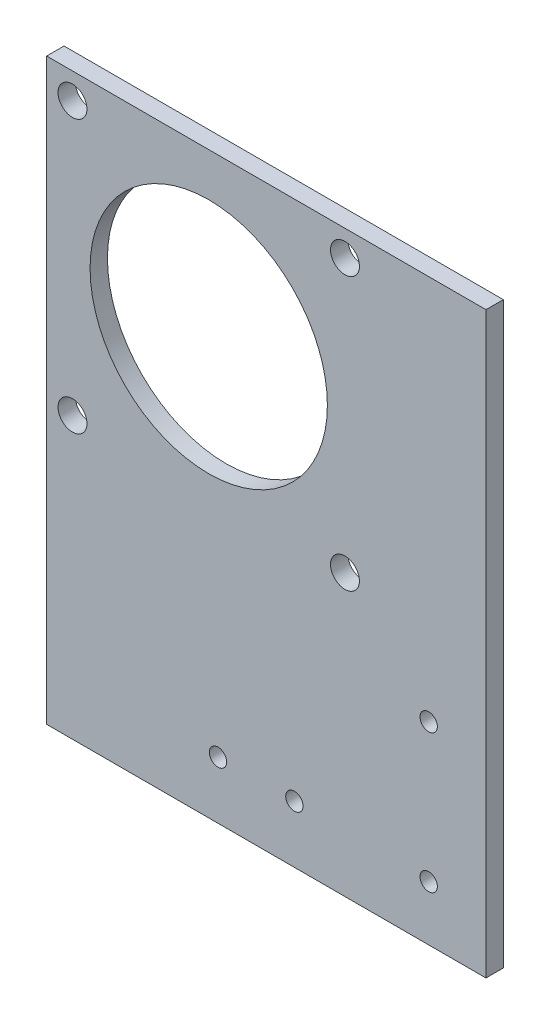
SolidWorks part; units mm, degrees
ref_plane "Front Plane" through (0, 0, 0) normal (0, 0, 1) x (1, 0, 0)
ref_plane "Top Plane" through (0, 0, 0) normal (0, 1, 0) x (1, 0, 0)
ref_plane "Right Plane" through (0, 0, 0) normal (1, 0, 0) x (0, 0, -1)
sketch "Sketch1" plane through (0, 0, 0) normal (0, 0, 1) x (1, 0, 0)
  line L1 (0, 0) -> (75.9, 0)
  line L2 (0, 0) -> (0, 100)
  line L3 (0, 100) -> (75.9, 100)
  line L4 (75.9, 0) -> (75.9, 100)
  dimension "D1" = 75.9
  dimension "D2" = 100
extrude "Boss-Extrude1" add sketch "Sketch1" along normal blind 3
sketch "Sketch2" plane through (0, 0, 0) normal (0, 0, -1) x (-1, 0, 0)
  circle A0 centre (-51.5386, 95.5386) radius 2.5
  circle A1 centre (-4.4614, 95.5386) radius 2.5
  circle A2 centre (-4.4614, 48.4614) radius 2.5
  circle A3 centre (-51.5386, 48.4614) radius 2.5
  dimension "D1" = 5
extrude "Cut-Extrude1" cut sketch "Sketch2" against normal blind 10
sketch "Sketch5" plane through (0, 0, 3) normal (0, 0, 1) x (1, 0, 0)
  line L0 (66, 0) -> (66, 100) construction
  line L1 (0, 0) -> (75.9, 0) construction
  line L2 (75.9, 100) -> (0, 100) construction
  line L3 (64.0784, 0) -> (67.9216, 0) construction
  line L4 (67.9216, 55.9706) -> (67.9216, -1564.0294) construction
  line L6 (64.0784, 55.9706) -> (64.0784, -1564.0294) construction
  circle A0 centre (66, 33.3914) radius 1.5
  circle A1 centre (66, 9.471) radius 1.5
  point P11 (66, 0)
  dimension "D1" = 3
extrude "Cut-Extrude2" cut sketch "Sketch5" against normal blind 10
sketch "Sketch7" plane through (0, 0, 0) normal (0, 0, -1) x (-1, 0, 0)
  circle A0 centre (-29.6, 9.9) radius 1.5
  circle A1 centre (-42.8, 9.9) radius 1.5
extrude "Cut-Extrude3" cut sketch "Sketch7" against normal blind 19.8
sketch "Sketch8" plane through (0, 0, 0) normal (0, 0, -1) x (-1, 0, 0)
  circle A0 centre (-28, 72) radius 20.5
  dimension "D1" = 41
extrude "Cut-Extrude4" cut sketch "Sketch8" against normal blind 19.8
